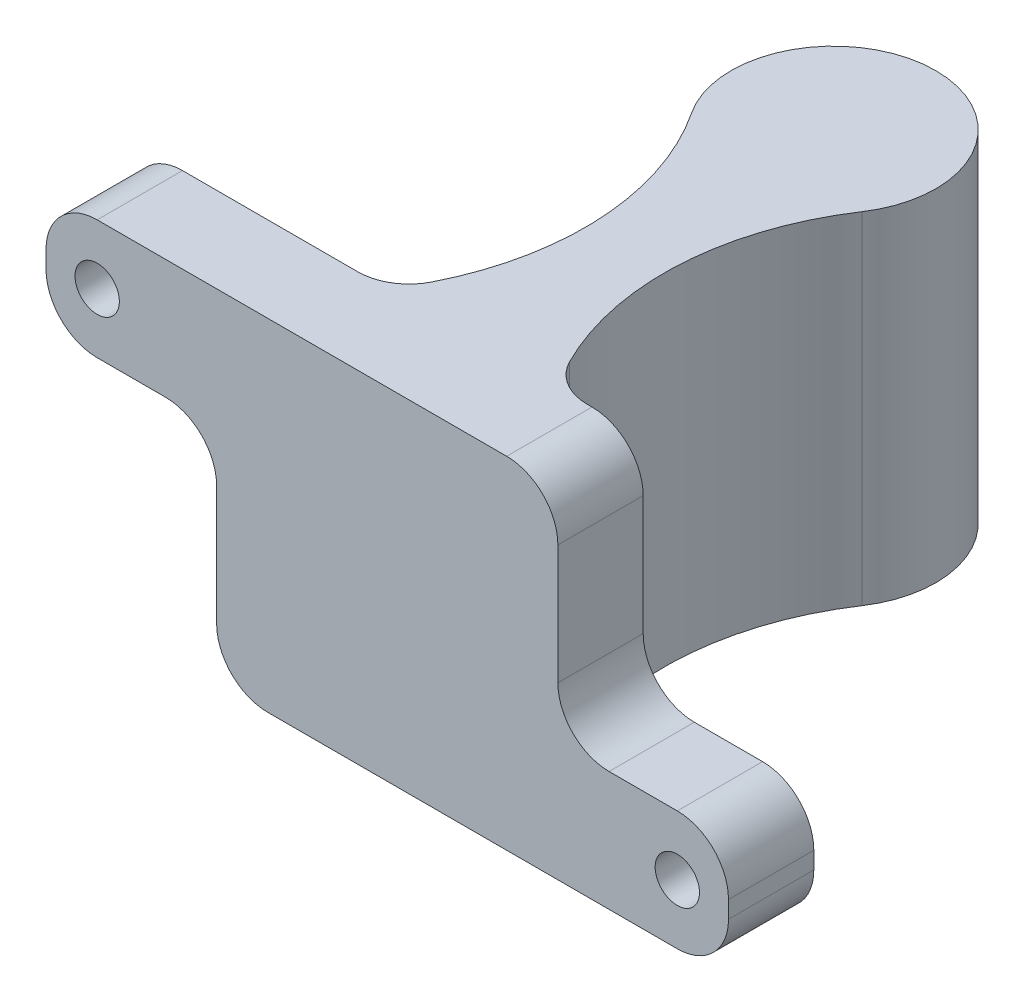
SolidWorks part; units mm, degrees
ref_plane "Front Plane" through (0, 0, 0) normal (0, 0, 1) x (1, 0, 0)
ref_plane "Top Plane" through (0, 0, 0) normal (0, 1, 0) x (1, 0, 0)
ref_plane "Right Plane" through (0, 0, 0) normal (1, 0, 0) x (0, 0, -1)
sketch "Sketch1" plane through (0, 0, 0) normal (0, 1, 0) x (1, 0, 0)
  line L0 (10, 26.15) -> (10, 0) construction
  line L1 (0, 0) -> (20, 0)
  line L2 (0, 0) -> (0, 35)
  line L3 (0, 35) -> (20, 35)
  line L4 (20, 0) -> (20, 35)
  circle A0 centre (10, 26.15) radius 3.3734
  point P7 (0, 0)
  point P9 (10, 35)
  dimension "D1" = 6.7469
  dimension "D2" = 26.15
  dimension "D3" = 35
  dimension "D4" = 20
extrude "Boss-Extrude1" add sketch "Sketch1" along normal blind 5
sketch "Sketch2" plane through (0, 5, 0) normal (0, 1, 0) x (1, 0, 0)
  line L0 (20, 0) -> (20, 35) construction
  line L1 (0, 0) -> (20, 0)
  line L2 (0, 0) -> (0, 5)
  line L3 (0, 5) -> (20, 5)
  line L4 (20, 0) -> (20, 5)
  dimension "D1" = 5
extrude "Boss-Extrude2" add sketch "Sketch2" along normal blind 20
sketch "Sketch3" plane through (0, 5, 0) normal (0, 1, 0) x (1, 0, 0)
  line L0 (20, 5) -> (0, 5) construction
  line L1 (5, 22.8334) -> (5, 5) construction
  line L2 (10, 26.15) -> (10, 5) construction
  line L3 (5, 5) -> (15, 5)
  arc A0 (15, 22.8334) -> (5, 22.8334) centre (10, 26.15) ccw
  arc A1 (5, 22.8334) -> (5, 5) centre (-8.4424, 13.9167) cw
  arc A2 (15, 22.8334) -> (15, 5) centre (28.4424, 13.9167) ccw
  circle A3 centre (10, 26.15) radius 3.3734
  circle A4 centre (10, 26.15) radius 3.3734 construction
  dimension "D1" = 12
  dimension "D2" = 5
extrude "Boss-Extrude3" add sketch "Sketch3" along normal blind 20
sketch "Sketch4" plane through (0, 0, 0) normal (0, -1, 0) x (1, 0, 0)
  line L1 (0, -35) -> (20, -35)
  line L2 (0, -35) -> (0, 0)
  line L3 (0, 0) -> (20, 0)
  line L4 (20, -35) -> (20, 0)
extrude "Cut-Extrude1" cut sketch "Sketch4" against normal up to surface (5 mm away) up to face at (10, 5, -18.1229)
sketch "Sketch5" plane through (0, 25, 0) normal (0, 1, 0) x (1, 0, 0)
  circle A0 centre (10, 26.15) radius 3.3734
  circle A1 centre (10, 26.15) radius 3.3734 construction
extrude "Boss-Extrude4" add sketch "Sketch5" against normal blind 3 contours A0
sketch "Sketch6" plane through (0, 0, 0) normal (0, 0, 1) x (1, 0, 0)
  line L0 (20, 5) -> (30, 5)
  line L1 (30, 5) -> (30, 12)
  line L2 (30, 12) -> (20, 12)
  line L3 (20, 25) -> (20, 5) construction
  line L4 (20, 12) -> (20, 5)
  line L5 (0, 25) -> (-10, 25)
  line L6 (-10, 25) -> (-10, 18)
  line L7 (-10, 18) -> (0, 18)
  line L8 (0, 25) -> (0, 5) construction
  line L9 (0, 18) -> (0, 25)
  line L10 (-7, 21.5) -> (0, 21.5) construction
  line L11 (27, 8.5) -> (20, 8.5) construction
  circle A0 centre (-7, 21.5) radius 1.3
  circle A1 centre (27, 8.5) radius 1.3
  dimension "D7" = 2.6
  dimension "D1" = 7
  dimension "D2" = 10
  dimension "D3" = 10
  dimension "D4" = 7
  dimension "D5" = 7
  dimension "D6" = 7
extrude "Boss-Extrude5" add sketch "Sketch6" against normal up to surface (5 mm away) up to face at (2.5, 15, -5)
fillet "Fillet1" radius 3 10 edges at (30, 5, -2.5) (30, 12, -2.5) (20, 12, -2.5) (0, 18, -2.5) (-10, 18, -2.5) (-10, 25, -2.5) (5, 15, -5) (15, 15, -5) (20, 25, -2.5) (0, 5, -2.5)
